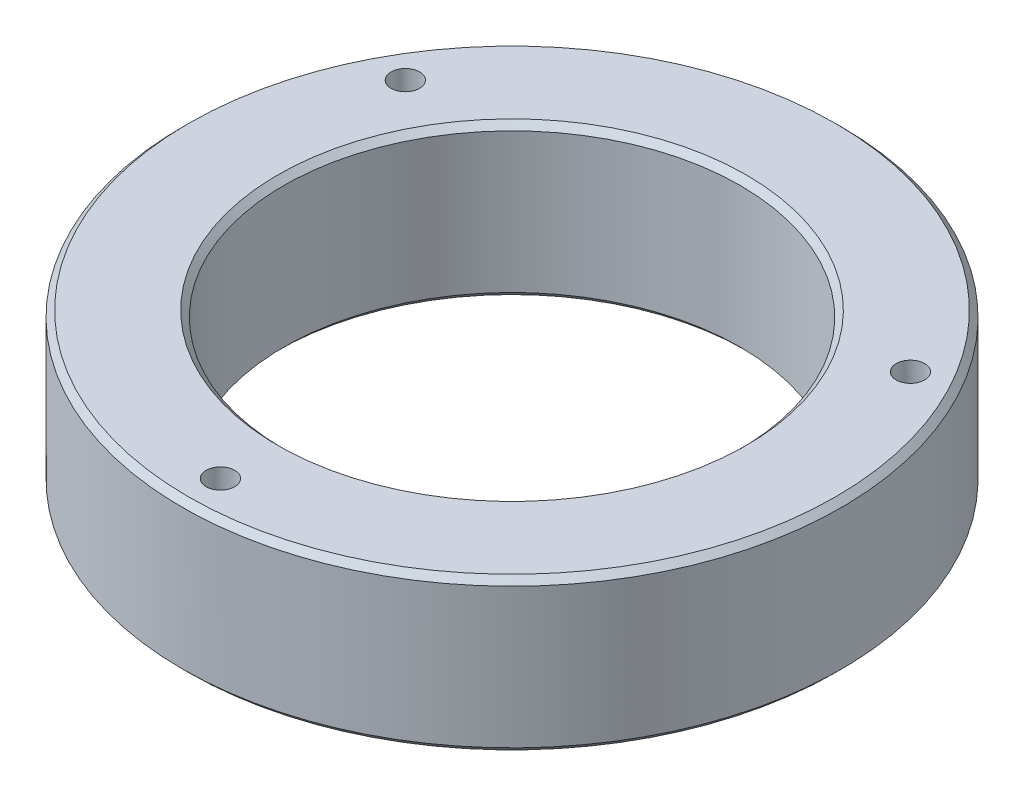
SolidWorks part; units mm, degrees
ref_plane "Front Plane" through (0, 0, 0) normal (1, 0, 0) x (0, 1, 0)
ref_plane "Top Plane" through (0, 0, 0) normal (0, 0, 1) x (0, 1, 0)
ref_plane "Right Plane" through (0, 0, 0) normal (0, 1, 0) x (-1, 0, 0)
sketch "Sketch1" plane through (0, 0, 0) normal (0, 0, 1) x (0, 1, 0)
  line L0 (-19.05, 82.5246) -> (19.05, 82.5246)
  line L1 (19.05, 82.5246) -> (19.05, 57.15)
  line L2 (19.05, 57.15) -> (-19.05, 57.15)
  line L3 (-19.05, 57.15) -> (-19.05, 82.5246)
  line L4 (-44.45, 0) -> (44.45, 0) construction
revolve "Revolve1" add sketch "Sketch1" angle 360 about L4
chamfer "Chamfer1" distance 1.524 angle 45 4 edges at (0, 19.05, -57.15) (0, -19.05, -57.15) (0, 19.05, -82.5246) (0, -19.05, -82.5246)
sketch "Sketch2" plane through (0, 0, 0) normal (0, 1, 0) x (-1, 0, 0)
  circle A0 centre (0, 73.025) radius 3.5687
extrude "Cut-Extrude2" cut sketch "Sketch2" along normal blind 76.2 from offset 19.05
sketch "Sketch3" plane through (0, 0, 0) normal (0, 1, 0) x (-1, 0, 0)
  circle A0 centre (0, 73.025) radius 5.5626
extrude "Cut-Extrude4" cut sketch "Sketch3" along normal blind 9.652 from offset 19.05
sketch "Sketch4" plane through (0, 0, 0) normal (0, 1, 0) x (-1, 0, 0)
  circle A0 centre (-63.246, -36.5252) radius 3.5687
extrude "Cut-Extrude6" cut sketch "Sketch4" along normal blind 76.2 from offset 19.05
sketch "Sketch5" plane through (0, 0, 0) normal (0, 1, 0) x (-1, 0, 0)
  circle A0 centre (-63.246, -36.5252) radius 5.5626
extrude "Cut-Extrude8" cut sketch "Sketch5" along normal blind 9.652 from offset 19.05
sketch "Sketch6" plane through (0, 0, 0) normal (0, 1, 0) x (-1, 0, 0)
  circle A0 centre (63.246, -36.5252) radius 3.5687
extrude "Cut-Extrude10" cut sketch "Sketch6" along normal blind 76.2 from offset 19.05
sketch "Sketch7" plane through (0, 0, 0) normal (0, 1, 0) x (-1, 0, 0)
  circle A0 centre (63.246, -36.5252) radius 5.5626
extrude "Cut-Extrude12" cut sketch "Sketch7" along normal blind 9.652 from offset 19.05
sketch "Sketch8" plane through (0, 0, 0) normal (0, 1, 0) x (-1, 0, 0)
  circle A0 centre (-69.85, 0) radius 3.9687
extrude "Cut-Extrude14" cut sketch "Sketch8" along normal blind 25.4 from offset 19.05
sketch "Sketch9" plane through (0, 0, 0) normal (0, 1, 0) x (-1, 0, 0)
  circle A0 centre (69.85, 0) radius 3.9687
extrude "Cut-Extrude16" cut sketch "Sketch9" along normal blind 25.4 from offset 19.05
